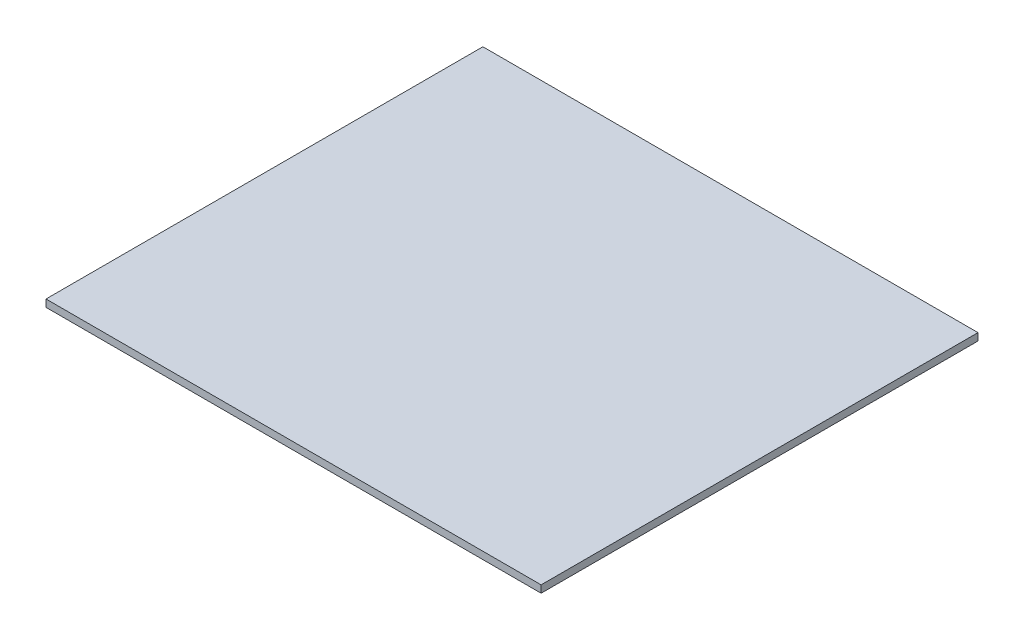
SolidWorks part; units mm, degrees
ref_plane "정면" through (0, 0, 0) normal (0, 0, 1) x (1, 0, 0)
ref_plane "윗면" through (0, 0, 0) normal (0, 1, 0) x (1, 0, 0)
ref_plane "우측면" through (0, 0, 0) normal (1, 0, 0) x (0, 0, -1)
sketch "스케치1" plane through (0, 0, 0) normal (0, 1, 0) x (1, 0, 0)
  line L1 (0, 0) -> (340, 0)
  line L2 (0, 0) -> (0, 300)
  line L3 (0, 300) -> (340, 300)
  line L4 (340, 0) -> (340, 300)
  dimension "D1" = 340
  dimension "D2" = 300
extrude "보스-돌출1" add sketch "스케치1" along normal blind 5
